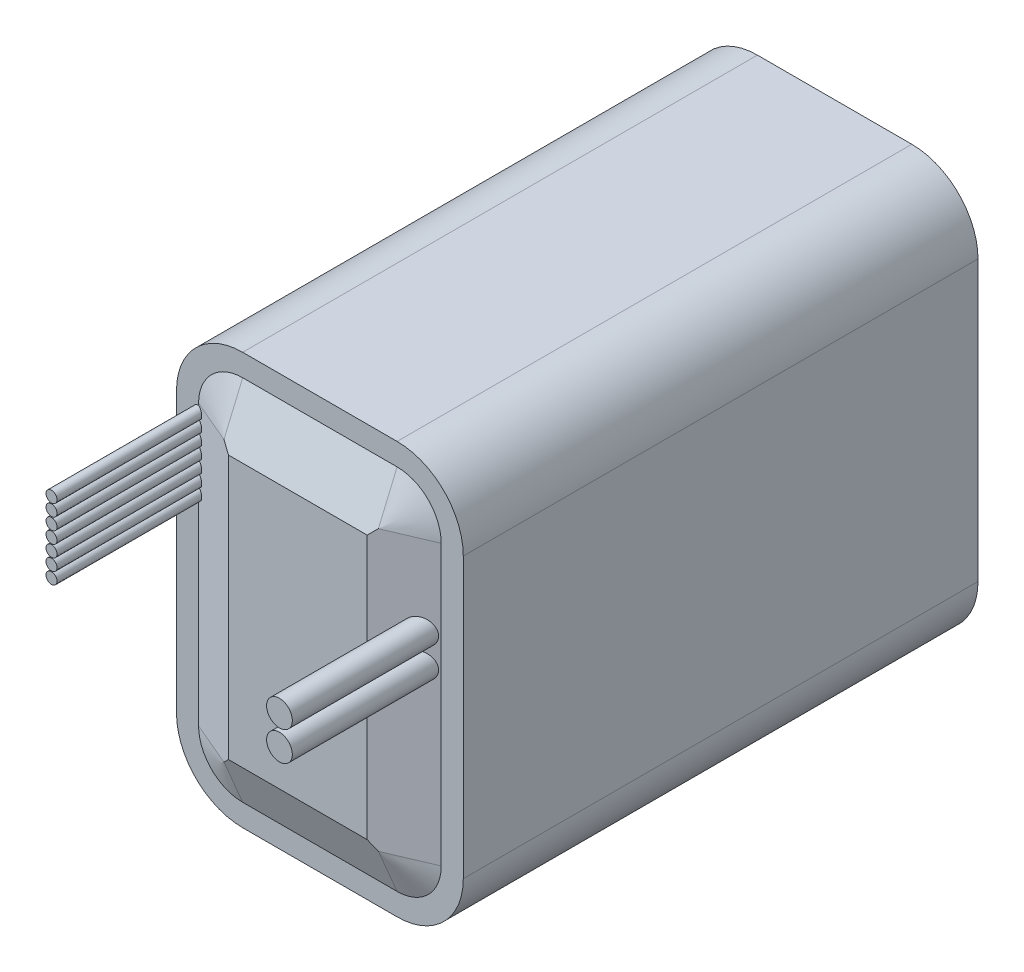
SolidWorks part; units mm, degrees
ref_plane "Front Plane" through (0, 0, 0) normal (1, 0, 0) x (0, 1, 0)
ref_plane "Top Plane" through (0, 0, 0) normal (0, 0, 1) x (0, 1, 0)
ref_plane "Right Plane" through (0, 0, 0) normal (0, 1, 0) x (-1, 0, 0)
sketch "Sketch1" plane through (0, 0, 0) normal (0, 0, 1) x (0, 1, 0)
  line L1 (-19, 19.5) -> (19, 19.5)
  line L2 (-28, 10.5) -> (-28, -10.5)
  line L3 (-19, -19.5) -> (19, -19.5)
  line L4 (28, 10.5) -> (28, -10.5)
  line L5 (-28, 19.5) -> (28, -19.5) construction
  line L6 (-28, -19.5) -> (28, 19.5) construction
  arc A0 (19, -19.5) -> (28, -10.5) centre (19, -10.5) ccw
  arc A1 (-28, -10.5) -> (-19, -19.5) centre (-19, -10.5) ccw
  arc A2 (-19, 19.5) -> (-28, 10.5) centre (-19, 10.5) ccw
  arc A3 (19, 19.5) -> (28, 10.5) centre (19, 10.5) cw
  point P0 (0, 0)
  dimension "D1" = 9
  dimension "D2" = 39
  dimension "D3" = 56
extrude "Boss-Extrude1" add sketch "Sketch1" along normal blind 70
sketch "Sketch2" plane through (0, 0, 70) normal (0, 0, 1) x (1, 0, 0)
  line L8 (10.5, 25) -> (-10.5, 25)
  line L9 (-16.5, 19) -> (-16.5, -19)
  line L10 (-10.5, -25) -> (10.5, -25)
  line L11 (16.5, -19) -> (16.5, 19)
  line L12 (10.5, 25) -> (-10.5, 25)
  line L13 (-16.5, 19) -> (-16.5, -19)
  line L14 (-10.5, -25) -> (10.5, -25)
  line L15 (16.5, -19) -> (16.5, 19)
  arc A8 (16.5, 19) -> (10.5, 25) centre (10.5, 19) ccw
  arc A9 (-10.5, 25) -> (-16.5, 19) centre (-10.5, 19) ccw
  arc A10 (-16.5, -19) -> (-10.5, -25) centre (-10.5, -19) ccw
  arc A11 (10.5, -25) -> (16.5, -19) centre (10.5, -19) ccw
  arc A12 (16.5, 19) -> (10.5, 25) centre (10.5, 19) ccw
  arc A13 (-10.5, 25) -> (-16.5, 19) centre (-10.5, 19) ccw
  arc A14 (-16.5, -19) -> (-10.5, -25) centre (-10.5, -19) ccw
  arc A15 (10.5, -25) -> (16.5, -19) centre (10.5, -19) ccw
  dimension "D1" = 3
extrude "Boss-Extrude2" add sketch "Sketch2" along normal blind 3 draft 67
sketch "Sketch3" plane through (0, 0, 70) normal (0, 0, 1) x (1, 0, 0)
  line L0 (19.5, -19) -> (19.5, 19) construction
  line L1 (10.5, 28) -> (-10.5, 28) construction
  line L2 (-19.5, 19) -> (-19.5, -19) construction
  line L4 (-16.5, 18) -> (-16.5, 16.4) construction
  circle A0 centre (14.5, 8) radius 1.75
  circle A1 centre (14.5, 4) radius 1.75
  circle A2 centre (-16.5, 18) radius 0.75
  circle A4 centre (-16.5, 16.4) radius 0.75
  circle A5 centre (-16.5, 14.8) radius 0.75
  circle A6 centre (-16.5, 13.2) radius 0.75
  circle A7 centre (-16.5, 11.6) radius 0.75
  circle A8 centre (-16.5, 10) radius 0.75
  circle A9 centre (-16.5, 8.4) radius 0.75
  dimension "D2" = 3.5
  dimension "D5" = 1.5
  dimension "D1" = 5
  dimension "D3" = 4
  dimension "D4" = 20
  dimension "D6" = 3
  dimension "D7" = 10
  dimension "D9" = 1.6
  dimension "D8" = 7
extrude "Boss-Extrude3" add sketch "Sketch3" along normal blind 20
